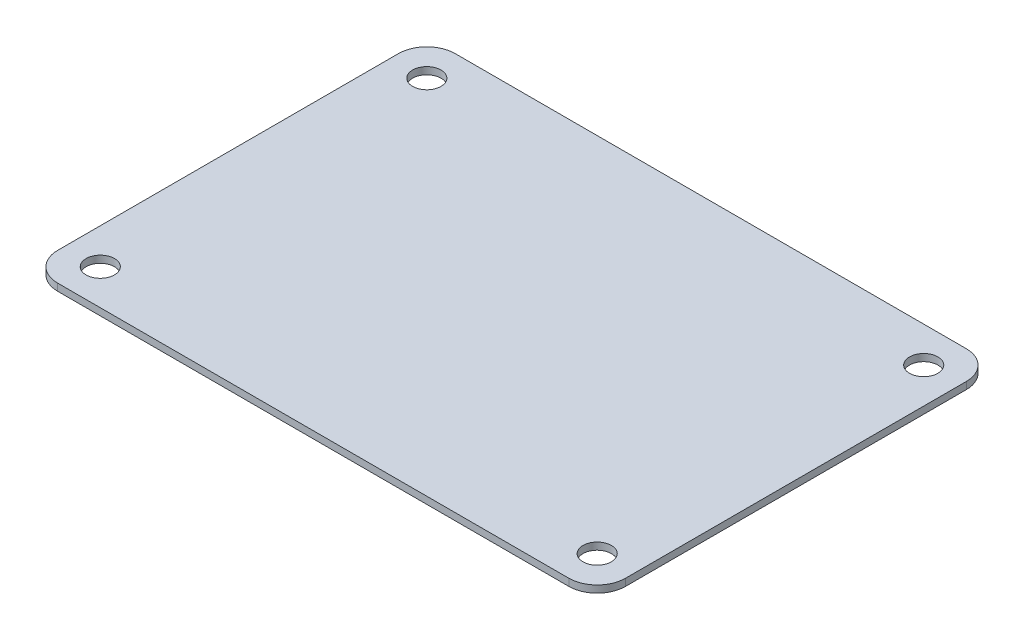
SolidWorks part; units mm, degrees
ref_plane "Front Plane" through (0, 0, 0) normal (0, 0, 1) x (1, 0, 0)
ref_plane "Top Plane" through (0, 0, 0) normal (0, 1, 0) x (1, 0, 0)
ref_plane "Right Plane" through (0, 0, 0) normal (1, 0, 0) x (0, 0, -1)
sketch "Sketch1" plane through (0, 0, 0) normal (0, 1, 0) x (1, 0, 0)
  line L1 (-127, 88.9) -> (127, 88.9)
  line L2 (-127, 88.9) -> (-127, -88.9)
  line L3 (-127, -88.9) -> (127, -88.9)
  line L4 (127, 88.9) -> (127, -88.9)
  circle A0 centre (-111.125, -73.025) radius 6.35
  circle A1 centre (-111.125, 73.025) radius 6.35
  circle A2 centre (111.125, 73.025) radius 6.35
  circle A3 centre (111.125, -73.025) radius 6.35
  point P4 (0, -88.9)
  point P5 (-127, 0)
  point P15 (0, 0)
  point P16 (0, 0)
  point P17 (0, 0)
  point P18 (0, 0)
  dimension "D3" = 12.7
  dimension "D1" = 254
  dimension "D2" = 177.8
  dimension "D4" = 15.875
  dimension "D5" = 15.875
  dimension "D6" = 15.875
  dimension "D7" = 15.875
extrude "Boss-Extrude1" add sketch "Sketch1" along normal blind 3.175
fillet "Fillet1" radius 12.7 4 edges at (-127, 1.5875, -88.9) (-127, 1.5875, 88.9) (127, 1.5875, -88.9) (127, 1.5875, 88.9)
